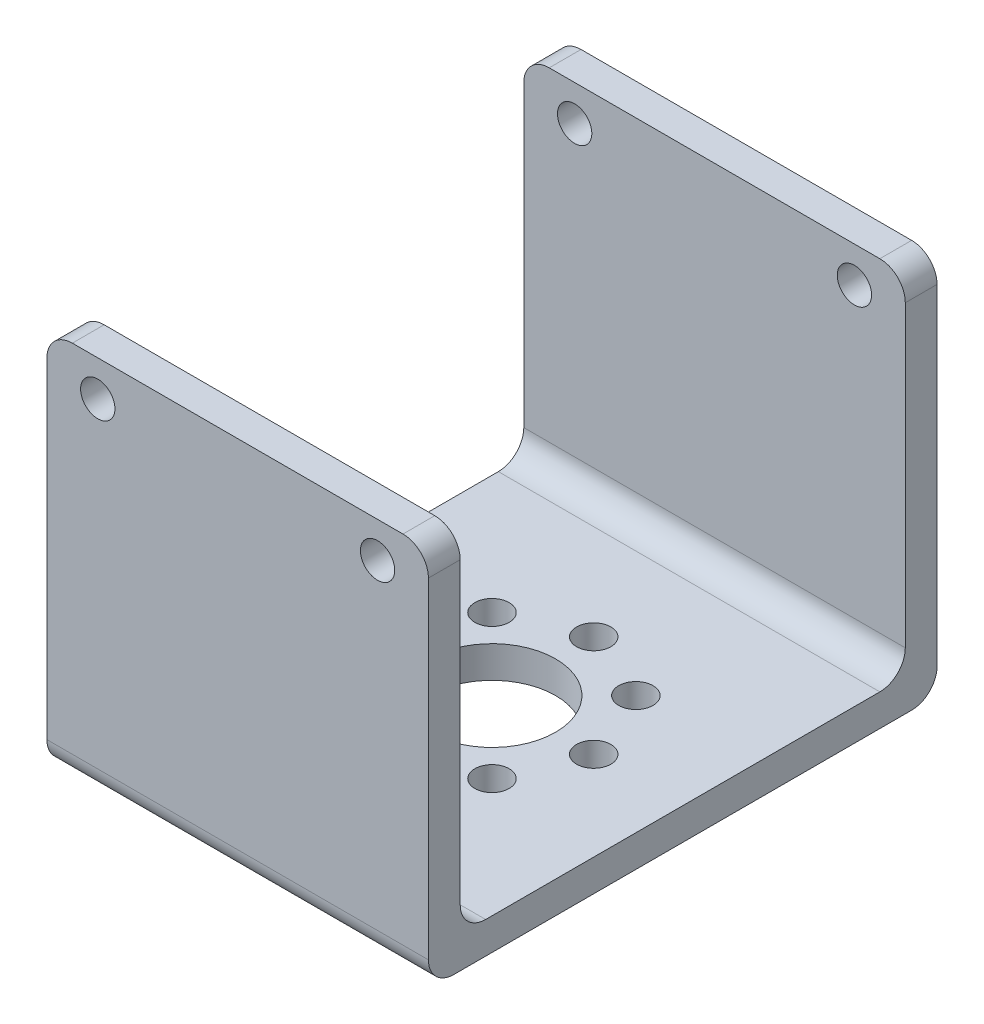
SolidWorks part; units mm, degrees
ref_plane "Plano frontal" through (0, 0, 0) normal (0, 0, 1) x (1, 0, 0)
ref_plane "Plano superior" through (0, 0, 0) normal (0, 1, 0) x (1, 0, 0)
ref_plane "Plano direito" through (0, 0, 0) normal (1, 0, 0) x (0, 0, -1)
sketch "Esboço1" plane through (0, 0, 0) normal (0, 0, 1) x (1, 0, 0)
  line L1 (-15, 15) -> (15, 15)
  line L2 (-15, 15) -> (-15, -15)
  line L3 (-15, -15) -> (15, -15)
  line L4 (15, 15) -> (15, -15)
  line L5 (-15, 15) -> (15, -15) construction
  line L6 (-15, -15) -> (15, 15) construction
  point P0 (0, 0)
  dimension "D1" = 30
  dimension "D2" = 30
extrude "Ressalto-extrusão1" add sketch "Esboço1" along normal blind 40
sketch "Esboço2" plane through (15, 0, 0) normal (1, 0, 0) x (0, 0, -1)
  line L0 (-40, 15) -> (-40, -15)
  line L1 (-40, -15) -> (0, -15)
  line L2 (0, -15) -> (0, 15)
  line L3 (-37.5, 15) -> (-37.5, -12.5)
  line L4 (-37.5, -12.5) -> (-2.5, -12.5)
  line L5 (-2.5, -12.5) -> (-2.5, 15)
  line L6 (-37.5, 15) -> (-2.5, 15)
  line M3 (0, 15) -> (-40, 15)
  dimension "D1" = 2.5
extrude "Corte-extrusão1" cut sketch "Esboço2" against normal blind 40 contours L4 L5 L3 M3
fillet "Filete1" radius 2 4 edges at (15, 15, 38.75) (-15, 15, 38.75) (-15, 15, 1.25) (15, 15, 1.25)
fillet "Filete2" radius 2 4 edges at (0, -12.5, 37.5) (0, -12.5, 2.5) (0, -15, 40) (0, -15, 0)
sketch "Esboço4" plane through (0, -15, 0) normal (0, -1, 0) x (-1, 0, 0)
  line L0 (-15, -38) -> (-15, -2) construction
  line L2 (-15, 0) -> (15, 0) construction
  circle A0 centre (0, -20) radius 5
  dimension "D1" = 10
  dimension "D2" = 15
  dimension "D3" = 20
extrude "Corte-extrusão3" cut sketch "Esboço4" against normal through all
sketch "Esboço5" plane through (0, -15, 0) normal (0, -1, 0) x (-1, 0, 0)
  line L0 (-5, -20) -> (0, -20)
  circle A0 centre (0, -20) radius 5 construction
  circle A1 centre (0, -28) radius 1.35
  circle A2 centre (-8, -20) radius 1.35
  circle A3 centre (0, -12) radius 1.35
  circle A4 centre (8, -20) radius 1.35
  circle A6 centre (-5.6569, -14.3431) radius 1.35
  circle A7 centre (5.6569, -14.3431) radius 1.35
  circle A8 centre (5.6569, -25.6569) radius 1.35
  circle A9 centre (-5.6569, -25.6569) radius 1.35
  dimension "D2" = 8
  dimension "D3" = 8
  dimension "D4" = 8
  dimension "D5" = 8
  dimension "D6" = 8
  dimension "D7" = 8
  dimension "D8" = 8
  dimension "D9" = 2.7
  dimension "D10" = 2.7
  dimension "D11" = 2.7
  dimension "D12" = 2.7
  dimension "D13" = 2.7
  dimension "D14" = 2.7
  dimension "D15" = 2.7
  dimension "D16" = 2.7
  dimension "D17" = 8
  dimension "D18" = 6.1229
  dimension "D19" = 6.1229
extrude "Corte-extrusão5" cut sketch "Esboço5" against normal through all contours A1 | A9 | A2 | A6 | A3 | A7 | A4 | A8
sketch "Esboço7" plane through (0, 0, 0) normal (0, 0, -1) x (-1, 0, 0)
  line L0 (-15, -13) -> (-15, 13) construction
  line L1 (15, 13) -> (15, -13) construction
  line L2 (-13, 15) -> (13, 15) construction
  circle A0 centre (-11, 12.2) radius 1.35
  circle A1 centre (11, 12.2) radius 1.35
  dimension "D1" = 2.7
  dimension "D2" = 2.7
  dimension "D3" = 4
  dimension "D4" = 4
  dimension "D5" = 2.8
  dimension "D6" = 2.8
extrude "Corte-extrusão6" cut sketch "Esboço7" against normal through all
